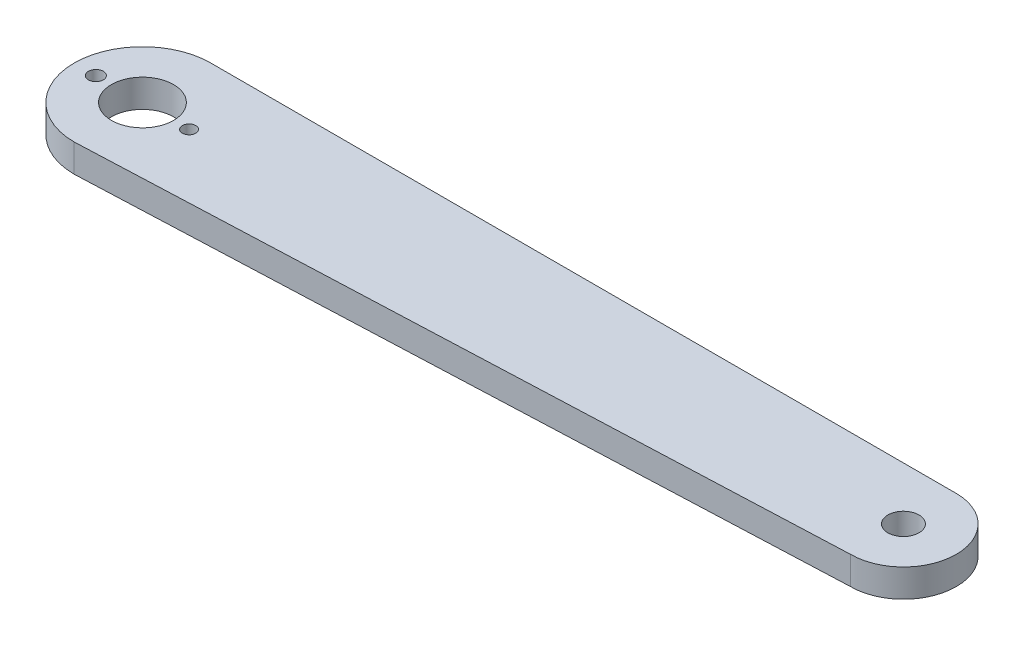
SolidWorks part; units mm, degrees
ref_plane "Front Plane" through (0, 0, 0) normal (0, 0, 1) x (1, 0, 0)
ref_plane "Top Plane" through (0, 0, 0) normal (0, 1, 0) x (1, 0, 0)
ref_plane "Right Plane" through (0, 0, 0) normal (1, 0, 0) x (0, 0, -1)
sketch "Sketch1" plane through (0, 0, 0) normal (0, 1, 0) x (1, 0, 0)
  line L1 (-119.974, 8.5) -> (0, 8.5)
  line L2 (-119.974, -13.5) -> (0, -8.5)
  circle A0 centre (0, 0) radius 2.5
  circle A1 centre (0, 0) radius 8.5
  circle A3 centre (-119.974, -2.5) radius 11
  circle A4 centre (-119.974, -2.5) radius 5
  circle A5 centre (-127.474, -2.5) radius 1.2012
  circle A6 centre (-112.474, -2.5) radius 1.0762
  point P15 (-126.1008, -5.8492)
  dimension "D1" = 5
  dimension "D2" = 17
  dimension "D3" = 7.5
  dimension "D4" = 22
  dimension "D5" = 10
  dimension "D6" = 0
  dimension "D7" = 0
  dimension "D8" = 120
  dimension "D9" = 7.5
extrude "Boss-Extrude2" add sketch "Sketch1" along normal blind 4.5
